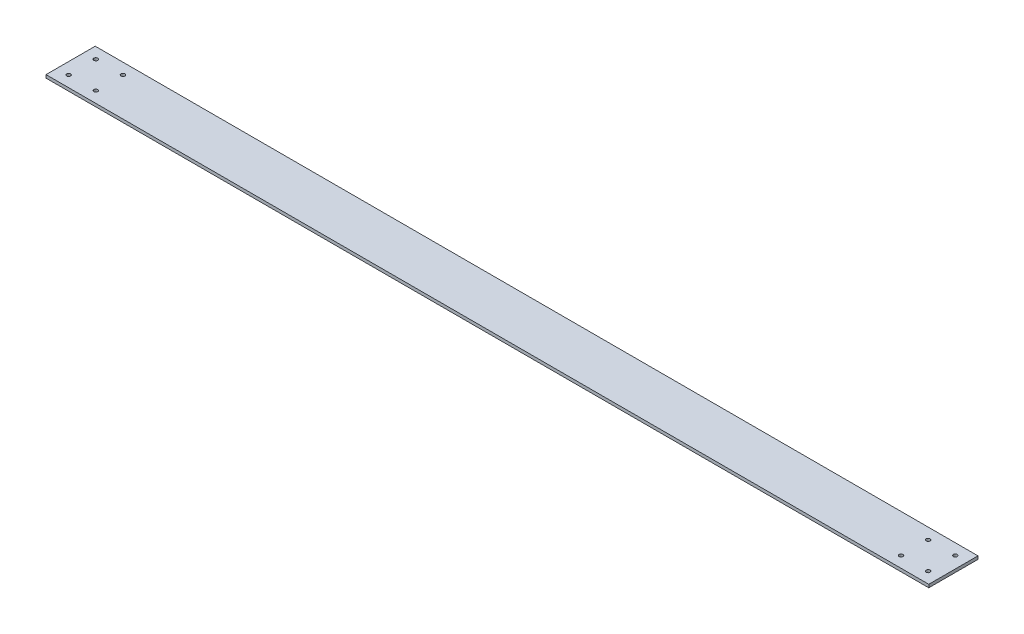
SolidWorks part; units mm, degrees
ref_plane "Front Plane" through (0, 0, 0) normal (0, 0, 1) x (1, 0, 0)
ref_plane "Top Plane" through (0, 0, 0) normal (0, 1, 0) x (1, 0, 0)
ref_plane "Right Plane" through (0, 0, 0) normal (1, 0, 0) x (0, 0, -1)
sketch "Sketch1" plane through (0, 0, 0) normal (0, 1, 0) x (1, 0, 0)
  line L1 (0, 0) -> (910.88, 0)
  line L2 (0, 0) -> (0, 50.8)
  line L3 (0, 50.8) -> (910.88, 50.8)
  line L4 (910.88, 0) -> (910.88, 50.8)
  circle A0 centre (12, 39.4) radius 2
  circle A1 centre (12, 11.4) radius 2
  circle A2 centre (898.88, 39.4) radius 2
  circle A3 centre (898.88, 11.4) radius 2
  circle A4 centre (40, 39.4) radius 2
  circle A5 centre (40, 11.4) radius 2
  circle A6 centre (870.88, 39.4) radius 2
  circle A7 centre (870.88, 11.4) radius 2
  dimension "D3" = 4
  dimension "D6" = 4
  dimension "D8" = 4
  dimension "D9" = 4
  dimension "D15" = 4
  dimension "D16" = 4
  dimension "D22" = 4
  dimension "D24" = 4
  dimension "D1" = 50.8
  dimension "D2" = 910.88
  dimension "D4" = 12
  dimension "D5" = 28
  dimension "D7" = 11.4
  dimension "D10" = 28
  dimension "D11" = 11.4
  dimension "D12" = 12
  dimension "D13" = 12
  dimension "D14" = 12
  dimension "D17" = 28
  dimension "D18" = 28
  dimension "D19" = 11.4
  dimension "D20" = 28
  dimension "D21" = 28
  dimension "D23" = 11.4
  dimension "D25" = 28
  dimension "D26" = 28
extrude "Boss-Extrude1" add sketch "Sketch1" along normal blind 3.175
equation "\"D7@Sketch1\"=(\"D1@Sketch1\"-\"D5@Sketch1\")/2"
